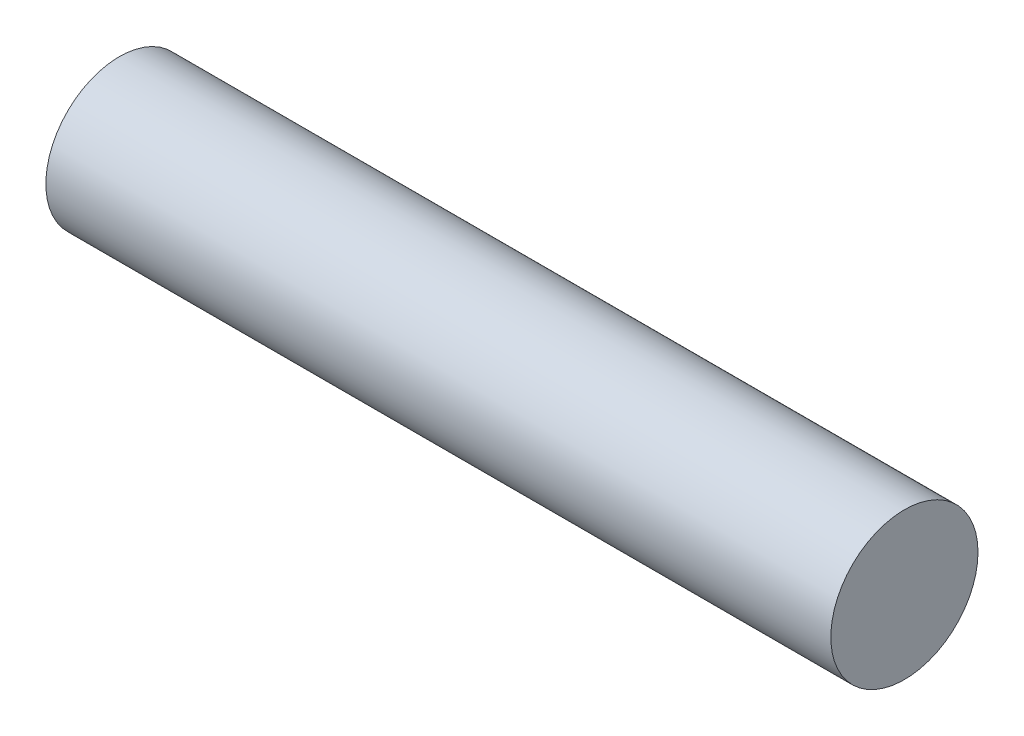
SolidWorks part; units mm, degrees
ref_plane "Plan de face" through (0, 0, 0) normal (0, 0, 1) x (1, 0, 0)
ref_plane "Plan de dessus" through (0, 0, 0) normal (0, 1, 0) x (1, 0, 0)
ref_plane "Plan de droite" through (0, 0, 0) normal (1, 0, 0) x (0, 0, -1)
sketch "Esquisse1" plane through (0, 0, 0) normal (1, 0, 0) x (0, 0, -1)
  circle A0 centre (0, 0) radius 15
  dimension "D1" = 30
extrude "Boss.-Extru.1" add sketch "Esquisse1" along normal blind 160
